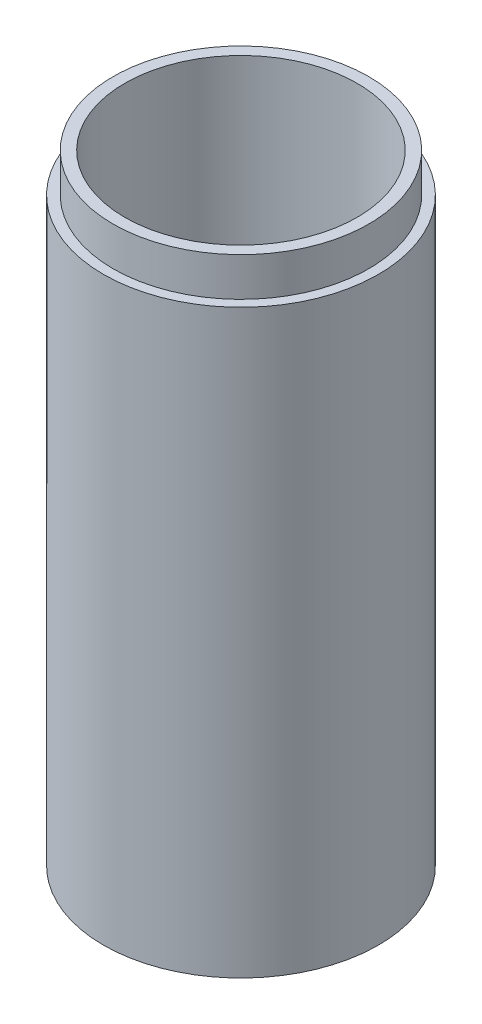
SolidWorks part; units mm, degrees
ref_plane "Front Plane" through (0, 0, 0) normal (0, 0, 1) x (1, 0, 0)
ref_plane "Top Plane" through (0, 0, 0) normal (0, 1, 0) x (1, 0, 0)
ref_plane "Right Plane" through (0, 0, 0) normal (1, 0, 0) x (0, 0, -1)
sketch "Sketch1" plane through (0, 0, 0) normal (0, 1, 0) x (1, 0, 0)
  circle A0 centre (0, 0) radius 17.75
  circle A1 centre (0, 0) radius 15
  dimension "D1" = 35.5
  dimension "D2" = 30
extrude "Boss-Extrude1" add sketch "Sketch1" along normal blind 75
sketch "Sketch2" plane through (0, 75, 0) normal (0, 1, 0) x (1, 0, 0)
  circle A0 centre (0, 0) radius 15
  circle A1 centre (0, 0) radius 16.5
  circle A2 centre (0, 0) radius 15 construction
  dimension "D1" = 33
extrude "Boss-Extrude2" add sketch "Sketch2" along normal blind 5
